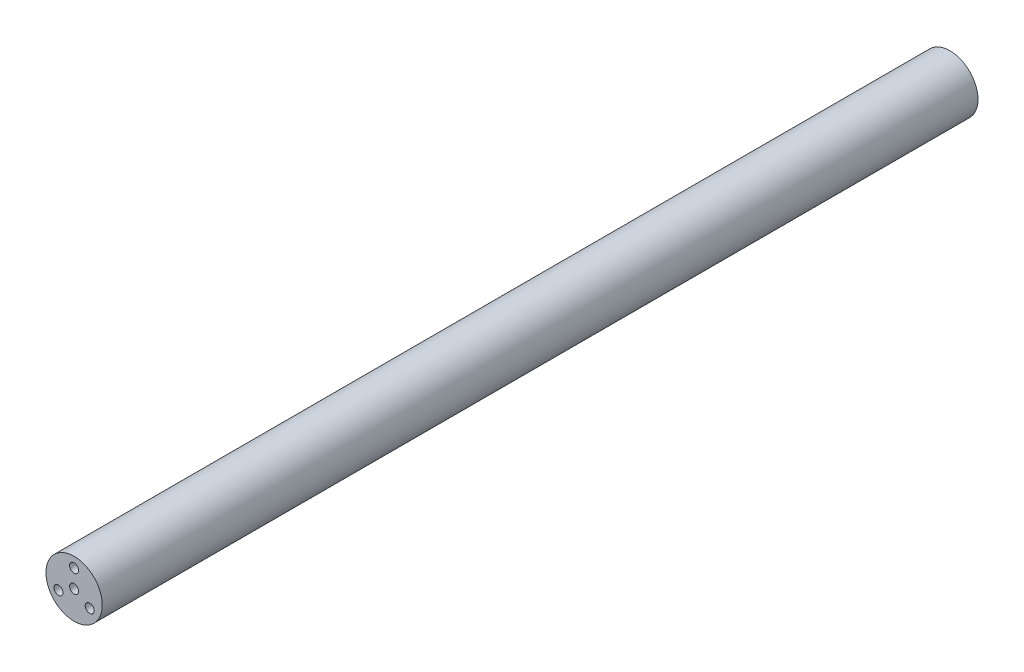
SolidWorks part; units mm, degrees
ref_plane "前视基准面" through (0, 0, 0) normal (0, 0, 1) x (1, 0, 0)
ref_plane "上视基准面" through (0, 0, 0) normal (0, 1, 0) x (1, 0, 0)
ref_plane "右视基准面" through (0, 0, 0) normal (1, 0, 0) x (0, 0, -1)
sketch "草图1" plane through (0, 0, 0) normal (0, 0, 1) x (1, 0, 0)
  circle A0 centre (0, 0) radius 12.5
  dimension "D1" = 25
extrude "凸台-拉伸1" add sketch "草图1" along normal mid plane 389
sketch "草图2" plane through (0, 0, 194.5) normal (0, 0, 1) x (1, 0, 0)
  circle A0 centre (0, 0) radius 8
  dimension "D1" = 16
extrude "切除-拉伸1" cut sketch "草图2" against normal offset from surface (349 mm away) 40 up to face at (12.5, 0, -194.5)
sketch "草图3" plane through (0, 0, 194.5) normal (0, 0, 1) x (1, 0, 0)
  circle A0 centre (0, 0) radius 10
extrude "凸台-拉伸2" add sketch "草图3" against normal blind 40
sketch "草图4" plane through (0, 0, 194.5) normal (0, 0, 1) x (1, 0, 0)
  line L0 (0, 8) -> (0, 0) construction
  line L1 (0, 0) -> (-6.9282, -4) construction
  line L2 (0, 0) -> (6.9282, -4) construction
  circle A0 centre (0, 0) radius 8 construction
  circle A1 centre (0, 8) radius 2
  circle A2 centre (-6.9282, -4) radius 2
  circle A3 centre (6.9282, -4) radius 2
  circle A5 centre (0, 0) radius 2
  circle A6 centre (6.9282, -4) radius 3.6 construction
  circle A7 centre (0, 0) radius 3.6 construction
  circle A8 centre (-6.9282, -4) radius 3.6 construction
  circle A9 centre (0, 8) radius 3.6 construction
  dimension "D1" = 16
  dimension "D2" = 120
  dimension "D4" = 4
  dimension "D5" = 7.2
  dimension "D3" = 120
extrude "切除-拉伸2" cut sketch "草图4" against normal blind 1000
sketch "草图5" plane through (0, 0, 0) normal (0, 0, 1) x (1, 0, 0)
  circle A0 centre (0, 0) radius 8
  circle A1 centre (0, 0) radius 12.5
extrude "凸台-拉伸4" add sketch "草图5" against normal offset from surface (146.5 mm away) 8 up to face at (0, 0, -154.5)
sketch "草图7" plane through (0, 0, 0) normal (0, 0, 1) x (1, 0, 0)
  circle A0 centre (0, 0) radius 8
  circle A1 centre (0, 0) radius 11.6804
extrude "凸台-拉伸7" add sketch "草图7" along normal offset from surface (146.5 mm away) 8 up to face at (2, 0, 154.5)
